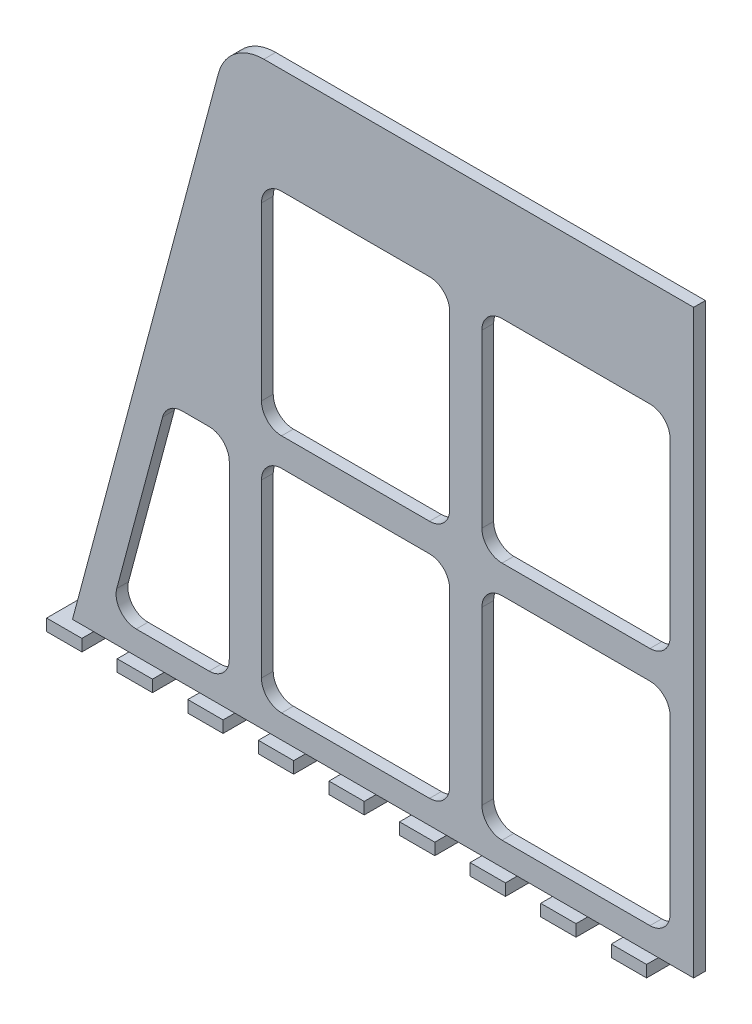
SolidWorks part; units mm, degrees
material "Balsa"
ref_plane "Front Plane" through (0, 0, 0) normal (0, 0, 1) x (1, 0, 0)
ref_plane "Top Plane" through (0, 0, 0) normal (0, 1, 0) x (1, 0, 0)
ref_plane "Right Plane" through (0, 0, 0) normal (1, 0, 0) x (0, 0, -1)
sketch "Sketch1" plane through (0, 0, 0) normal (0, 0, 1) x (1, 0, 0)
  line L0 (0, 0) -> (335.28, 0)
  line L1 (335.28, 0) -> (335.28, 313.5173)
  line L2 (335.28, 313.5173) -> (103.3213, 313.5173)
  line L3 (78.7832, 294.6776) -> (0, 0)
  arc A0 (103.3213, 313.5173) -> (78.7832, 294.6776) centre (103.3213, 288.1173) ccw
  point P8 (83.82, 313.5173)
  point P11 (335.28, 313.5173)
  dimension "D4" = 25.4
  dimension "D1" = 335.28
  dimension "D2" = 313.5173
  dimension "D3" = 251.46
extrude "Boss-Extrude1" add sketch "Sketch1" along normal blind 6.35
sketch "Sketch2" plane through (0, 0, 6.35) normal (0, 0, 1) x (1, 0, 0)
  line L0 (335.28, 0) -> (335.28, 313.5173) construction
  line L1 (311.7054, 12.7) -> (231.8546, 12.7)
  line L2 (322.58, 23.5746) -> (322.58, 116.1254)
  line L3 (311.7054, 127) -> (231.8546, 127)
  line L4 (220.98, 23.5746) -> (220.98, 116.1254)
  line L5 (0, 0) -> (335.28, 0) construction
  line L6 (203.6033, 23.5746) -> (203.6033, 116.1254)
  line L7 (192.7288, 12.7) -> (112.8779, 12.7)
  line L8 (102.0033, 23.5746) -> (102.0033, 116.1254)
  line L9 (192.7288, 127) -> (112.8779, 127)
  line L10 (84.6266, 23.5746) -> (84.6266, 116.1254)
  line L11 (73.7521, 12.7) -> (34.4142, 12.7)
  line L13 (73.7521, 127) -> (59.158, 127)
  line L14 (203.6033, 153.1146) -> (203.6033, 245.6654)
  line L15 (192.7288, 142.24) -> (112.8779, 142.24)
  line L16 (102.0033, 153.1146) -> (102.0033, 245.6654)
  line L17 (192.7288, 256.54) -> (112.8779, 256.54)
  line L18 (84.6266, 153.1146) -> (84.6266, 251.1027)
  line L19 (73.7521, 142.24) -> (69.0472, 142.24)
  line L30 (322.58, 153.1146) -> (322.58, 245.6654)
  line L31 (311.7054, 142.24) -> (231.8546, 142.24)
  line L32 (220.98, 153.1146) -> (220.98, 245.6654)
  line L33 (311.7054, 256.54) -> (231.8546, 256.54)
  line L38 (84.6266, 253.4908) -> (58.5416, 155.9233)
  line L40 (78.7832, 294.6776) -> (0, 0) construction
  line L41 (-16.9734, 12.7) -> (-16.9734, 127) [skipped]
  line L42 (-16.9734, 136.8027) -> (-16.9734, 251.1027) [skipped]
  line L43 (84.6266, 256.54) -> (-16.9734, 256.54) [skipped]
  line L44 (48.6524, 118.9342) -> (23.9086, 26.3833)
  line L45 (84.6266, 271.78) -> (84.6266, 386.08) [skipped]
  line L46 (84.6266, 386.08) -> (-16.9734, 386.08) [skipped]
  line L47 (-16.9734, 271.78) -> (-16.9734, 386.08) [skipped]
  line L48 (84.6266, 271.78) -> (-16.9734, 271.78) [skipped]
  line L49 (203.6033, 271.78) -> (203.6033, 386.08) [skipped]
  line L50 (203.6033, 386.08) -> (102.0033, 386.08) [skipped]
  line L51 (102.0033, 271.78) -> (102.0033, 386.08) [skipped]
  line L52 (203.6033, 271.78) -> (102.0033, 271.78) [skipped]
  line L53 (322.58, 271.78) -> (322.58, 386.08) [skipped]
  line L54 (322.58, 386.08) -> (220.98, 386.08) [skipped]
  line L55 (220.98, 271.78) -> (220.98, 386.08) [skipped]
  line L56 (322.58, 271.78) -> (220.98, 271.78) [skipped]
  arc A0 (69.0472, 142.24) -> (58.5416, 155.9233) centre (69.0472, 153.1146) cw
  arc A1 (84.6266, 153.1146) -> (73.7521, 142.24) centre (73.7521, 153.1146) cw
  arc A2 (84.6266, 23.5746) -> (73.7521, 12.7) centre (73.7521, 23.5746) cw
  arc A3 (34.4142, 12.7) -> (23.9086, 26.3833) centre (34.4142, 23.5746) cw
  arc A4 (59.158, 127) -> (48.6524, 118.9342) centre (59.158, 116.1254) ccw
  arc A5 (84.6266, 116.1254) -> (73.7521, 127) centre (73.7521, 116.1254) ccw
  arc A6 (102.0033, 116.1254) -> (112.8779, 127) centre (112.8779, 116.1254) cw
  arc A7 (112.8779, 12.7) -> (102.0033, 23.5746) centre (112.8779, 23.5746) cw
  arc A8 (203.6033, 23.5746) -> (192.7288, 12.7) centre (192.7288, 23.5746) cw
  arc A9 (203.6033, 116.1254) -> (192.7288, 127) centre (192.7288, 116.1254) ccw
  arc A10 (231.8546, 127) -> (220.98, 116.1254) centre (231.8546, 116.1254) ccw
  arc A11 (231.8546, 12.7) -> (220.98, 23.5746) centre (231.8546, 23.5746) cw
  arc A12 (311.7054, 12.7) -> (322.58, 23.5746) centre (311.7054, 23.5746) ccw
  arc A13 (322.58, 116.1254) -> (311.7054, 127) centre (311.7054, 116.1254) ccw
  arc A14 (322.58, 153.1146) -> (311.7054, 142.24) centre (311.7054, 153.1146) cw
  arc A15 (322.58, 245.6654) -> (311.7054, 256.54) centre (311.7054, 245.6654) ccw
  arc A16 (220.98, 245.6654) -> (231.8546, 256.54) centre (231.8546, 245.6654) cw
  arc A17 (231.8546, 142.24) -> (220.98, 153.1146) centre (231.8546, 153.1146) cw
  arc A18 (112.8779, 142.24) -> (102.0033, 153.1146) centre (112.8779, 153.1146) cw
  arc A19 (203.6033, 153.1146) -> (192.7288, 142.24) centre (192.7288, 153.1146) cw
  arc A20 (203.6033, 245.6654) -> (192.7288, 256.54) centre (192.7288, 245.6654) ccw
  arc A21 (102.0033, 245.6654) -> (112.8779, 256.54) centre (112.8779, 245.6654) cw
  point P33 (50.8088, 127)
  point P83 (220.98, 127)
  point P86 (220.98, 12.7)
  point P91 (322.58, 127)
  dimension "D7" = 10.8746
  dimension "D1" = 114.3
  dimension "D2" = 101.6
  dimension "D3" = 12.7
  dimension "D4" = 12.7
  dimension "D5" = 3
  dimension "D6" = 3
extrude "Cut-Extrude1" cut sketch "Sketch2" along direction (0, 0, 1) on the side against the normal up to surface (6.35 mm away) contours L18 L38 L19 | L14 L17 L16 L15 | L13 L44 L11 L10 | L6 L9 L8 L7 | L4 L1 L2 L3 | L30 L33 L32 L31
sketch "Sketch3" plane through (0, 0, 6.35) normal (0, 0, 1) x (1, 0, 0)
  line L0 (316.23, 0) -> (316.23, -6.35)
  line L1 (335.28, 0) -> (316.23, 0)
  line L2 (335.28, 0) -> (335.28, -6.35)
  line L3 (335.28, -6.35) -> (316.23, -6.35)
  line L4 (316.23, 0) -> (316.23, -6.35)
  line L5 (316.23, 0) -> (297.18, 0)
  line L6 (297.18, 0) -> (297.18, -6.35)
  line L7 (316.23, -6.35) -> (297.18, -6.35)
  line L8 (297.18, 0) -> (297.18, -6.35)
  line L9 (297.18, 0) -> (278.13, 0)
  line L10 (278.13, 0) -> (278.13, -6.35)
  line L11 (297.18, -6.35) -> (278.13, -6.35)
  line L12 (278.13, 0) -> (278.13, -6.35)
  line L13 (278.13, 0) -> (259.08, 0)
  line L14 (259.08, 0) -> (259.08, -6.35)
  line L15 (278.13, -6.35) -> (259.08, -6.35)
  line L16 (259.08, 0) -> (259.08, -6.35)
  line L17 (259.08, 0) -> (240.03, 0)
  line L18 (240.03, 0) -> (240.03, -6.35)
  line L19 (259.08, -6.35) -> (240.03, -6.35)
  line L20 (240.03, 0) -> (240.03, -6.35)
  line L21 (240.03, 0) -> (220.98, 0)
  line L22 (220.98, 0) -> (220.98, -6.35)
  line L23 (240.03, -6.35) -> (220.98, -6.35)
  line L24 (220.98, 0) -> (220.98, -6.35)
  line L25 (220.98, 0) -> (201.93, 0)
  line L26 (201.93, 0) -> (201.93, -6.35)
  line L27 (220.98, -6.35) -> (201.93, -6.35)
  line L28 (201.93, 0) -> (201.93, -6.35)
  line L29 (201.93, 0) -> (182.88, 0)
  line L30 (182.88, 0) -> (182.88, -6.35)
  line L31 (201.93, -6.35) -> (182.88, -6.35)
  line L32 (182.88, 0) -> (182.88, -6.35)
  line L33 (182.88, 0) -> (163.83, 0)
  line L34 (163.83, 0) -> (163.83, -6.35)
  line L35 (182.88, -6.35) -> (163.83, -6.35)
  line L36 (163.83, 0) -> (163.83, -6.35)
  line L37 (163.83, 0) -> (144.78, 0)
  line L38 (144.78, 0) -> (144.78, -6.35)
  line L39 (163.83, -6.35) -> (144.78, -6.35)
  line L40 (144.78, 0) -> (144.78, -6.35)
  line L41 (144.78, 0) -> (125.73, 0)
  line L42 (125.73, 0) -> (125.73, -6.35)
  line L43 (144.78, -6.35) -> (125.73, -6.35)
  line L44 (125.73, 0) -> (125.73, -6.35)
  line L45 (125.73, 0) -> (106.68, 0)
  line L46 (106.68, 0) -> (106.68, -6.35)
  line L47 (125.73, -6.35) -> (106.68, -6.35)
  line L48 (106.68, 0) -> (106.68, -6.35)
  line L49 (106.68, 0) -> (87.63, 0)
  line L50 (87.63, 0) -> (87.63, -6.35)
  line L51 (106.68, -6.35) -> (87.63, -6.35)
  line L52 (87.63, 0) -> (87.63, -6.35)
  line L53 (87.63, 0) -> (68.58, 0)
  line L54 (68.58, 0) -> (68.58, -6.35)
  line L55 (87.63, -6.35) -> (68.58, -6.35)
  line L56 (68.58, 0) -> (68.58, -6.35)
  line L57 (68.58, 0) -> (49.53, 0)
  line L58 (49.53, 0) -> (49.53, -6.35)
  line L59 (68.58, -6.35) -> (49.53, -6.35)
  line L60 (49.53, 0) -> (49.53, -6.35)
  line L61 (49.53, 0) -> (30.48, 0)
  line L62 (30.48, 0) -> (30.48, -6.35)
  line L63 (49.53, -6.35) -> (30.48, -6.35)
  line L64 (30.48, 0) -> (30.48, -6.35)
  line L65 (30.48, 0) -> (11.43, 0)
  line L66 (11.43, 0) -> (11.43, -6.35)
  line L67 (30.48, -6.35) -> (11.43, -6.35)
  line L68 (11.43, 0) -> (11.43, -6.35)
  line L69 (11.43, 0) -> (-7.62, 0)
  line L70 (-7.62, 0) -> (-7.62, -6.35)
  line L71 (11.43, -6.35) -> (-7.62, -6.35)
  line M22 (0, 0) -> (335.28, 0)
  dimension "D1" = 6.35
  dimension "D2" = 19.05
  dimension "D3" = 18
extrude "Boss-Extrude2" add sketch "Sketch3" against normal blind 12.7 and the other way blind 6.35 contours L71 L66 L69 L70 M22 | L63 L58 L62 M22 | L55 L50 L54 M22 | L47 L42 L46 M22 | L39 L34 L38 M22 | L31 L26 L30 M22 | L23 L18 L22 M22 | L15 L10 L14 M22 | L7 L0 L6 M22
sketch "Sketch4" plane through (335.28, 0, 0) normal (1, 0, 0) x (0, 0, -1)
  line L0 (-6.35, 0) -> (0, 0) construction
  point P0 (-3.175, 0)
